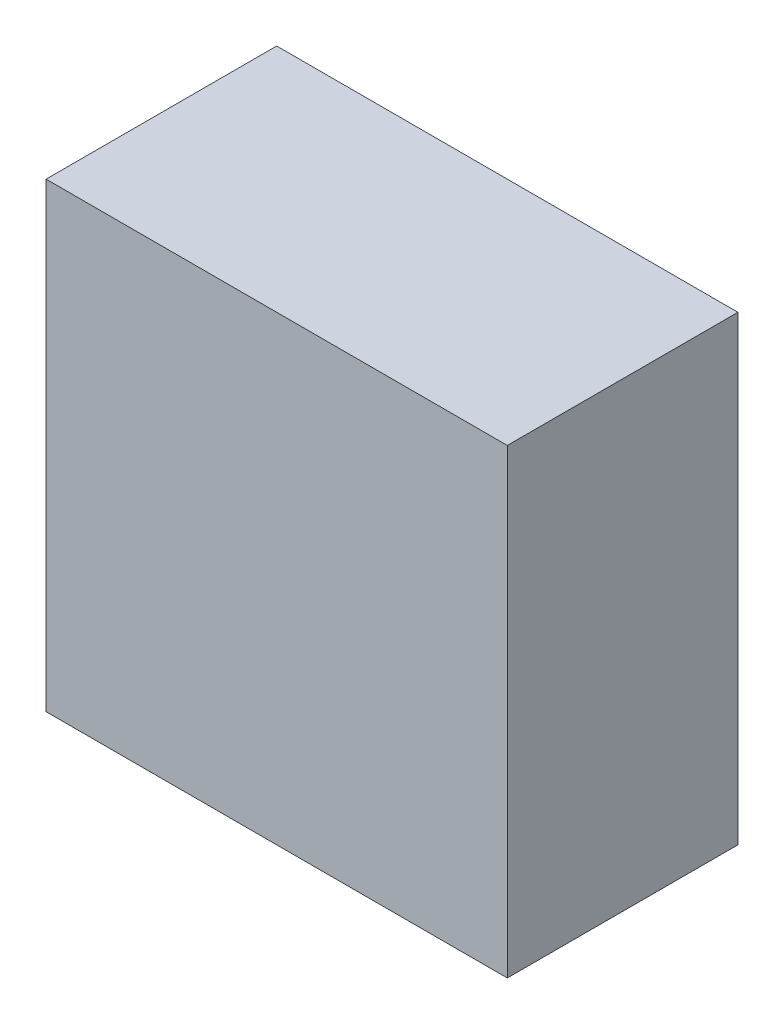
SolidWorks part; units mm, degrees
material "ABS"
ref_plane "Alzado" through (0, 0, 0) normal (0, 0, 1) x (1, 0, 0)
ref_plane "Planta" through (0, 0, 0) normal (0, 1, 0) x (1, 0, 0)
ref_plane "Vista lateral" through (0, 0, 0) normal (1, 0, 0) x (0, 0, -1)
sketch "Croquis1" plane through (0, 0, 0) normal (0, 0, 1) x (1, 0, 0)
  line L1 (-25.4, -25.4) -> (25.4, -25.4)
  line L2 (-25.4, -25.4) -> (-25.4, 25.4)
  line L3 (-25.4, 25.4) -> (25.4, 25.4)
  line L4 (25.4, -25.4) -> (25.4, 25.4)
  line L5 (-25.4, -25.4) -> (25.4, 25.4) construction
  line L6 (-25.4, 25.4) -> (25.4, -25.4) construction
  point P0 (0, 0)
  dimension "D1" = 50.8
  dimension "D2" = 50.8
extrude "Saliente-Extruir1" add sketch "Croquis1" along normal blind 25.4
